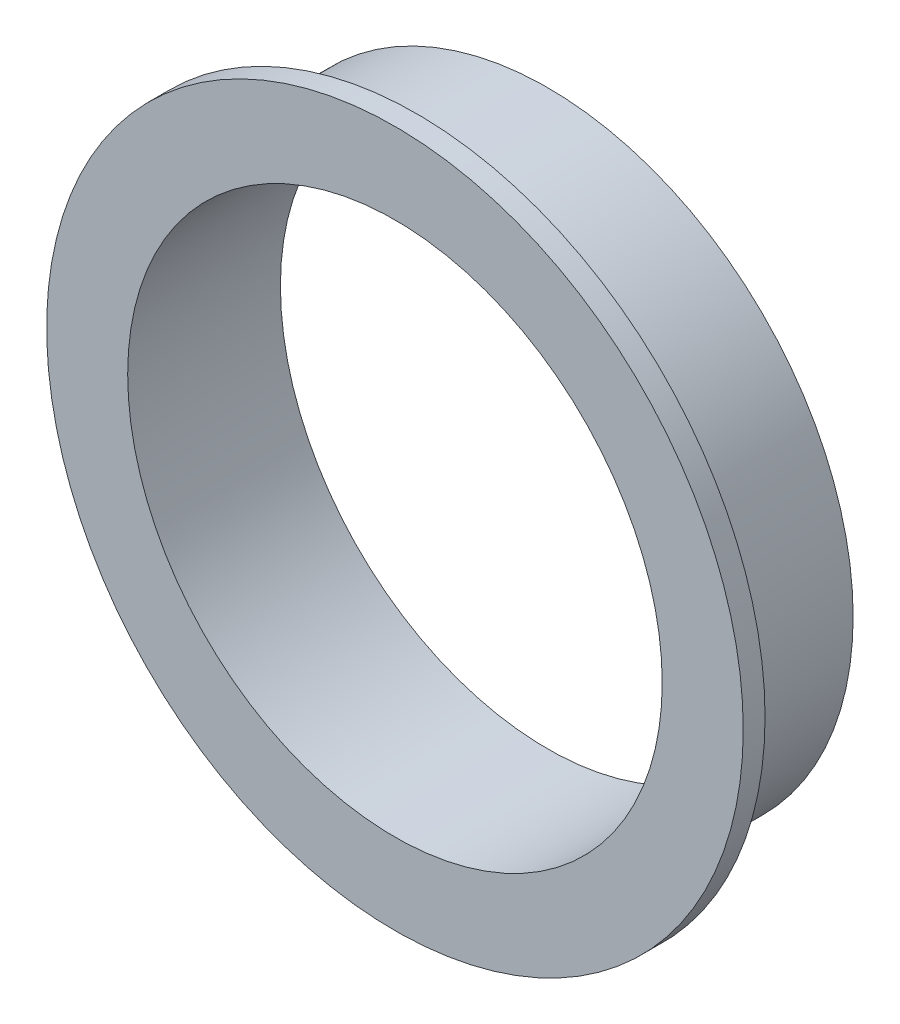
SolidWorks part; units mm, degrees
ref_plane "前视基准面" through (0, 0, 0) normal (0, 0, 1) x (1, 0, 0)
ref_plane "上视基准面" through (0, 0, 0) normal (0, 1, 0) x (1, 0, 0)
ref_plane "右视基准面" through (0, 0, 0) normal (1, 0, 0) x (0, 0, -1)
other "Configuration Table"
sketch "草图1" plane through (0, 0, 0) normal (0, 0, 1) x (1, 0, 0)
  circle A0 centre (0, 0) radius 12.25
  circle A1 centre (0, 0) radius 14
  dimension "D1" = 24.5
  dimension "D2" = 28
extrude "凸台-拉伸1" add sketch "草图1" along normal mid plane 6
sketch "草图2" plane through (0, 0, 3) normal (0, 0, 1) x (1, 0, 0)
  circle A0 centre (0, 0) radius 12.25
  circle A1 centre (0, 0) radius 15.963
extrude "凸台-拉伸2" add sketch "草图2" along normal blind 1
